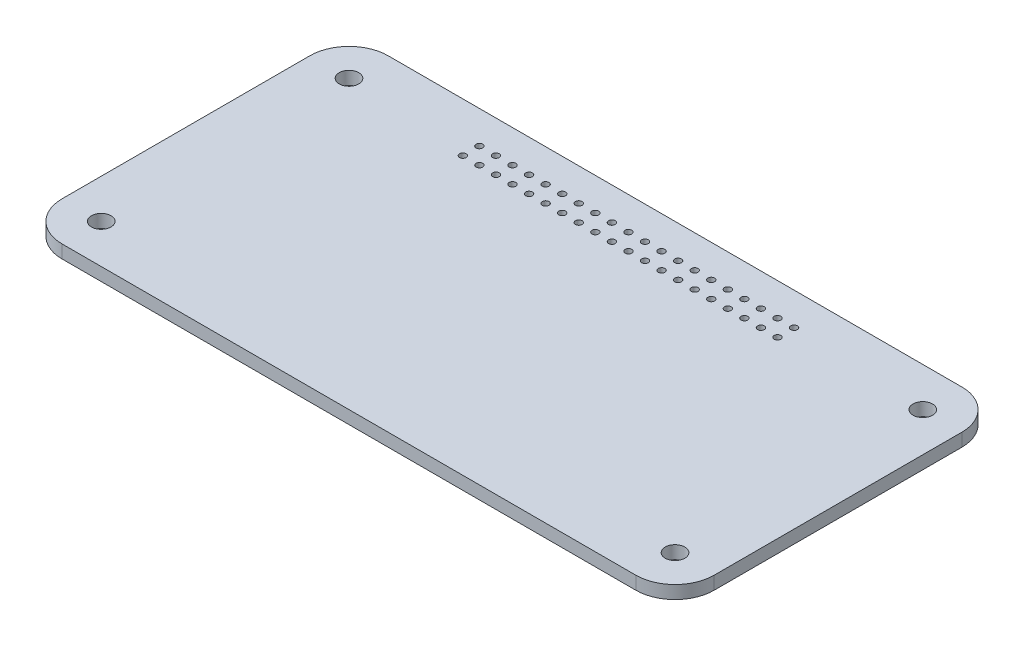
SolidWorks part; units mm, degrees
ref_plane "Front Plane" through (0, 0, 0) normal (0, 0, 1) x (1, 0, 0)
ref_plane "Top Plane" through (0, 0, 0) normal (0, 1, 0) x (1, 0, 0)
ref_plane "Right Plane" through (0, 0, 0) normal (1, 0, 0) x (0, 0, -1)
sketch "Sketch1" plane through (0, 0, 0) normal (0, 1, 0) x (1, 0, 0)
  line L1 (-50, -25) -> (50, -25)
  line L2 (-50, -25) -> (-50, 25)
  line L3 (-50, 25) -> (50, 25)
  line L4 (50, -25) -> (50, 25)
  line L5 (-50, -25) -> (50, 25) construction
  line L6 (-50, 25) -> (50, -25) construction
  point P0 (0, 0)
  dimension "D1" = 100
  dimension "D2" = 50
extrude "Boss-Extrude1" add sketch "Sketch1" along normal blind 2
fillet "Fillet1" radius 6 4 edges at (-50, 1, -25) (-50, 1, 25) (50, 1, -25) (50, 1, 25)
sketch "Sketch2" plane through (0, 2, 0) normal (0, 1, 0) x (1, 0, 0)
  line L0 (44, 25) -> (-44, 25) construction
  line L1 (-44, -19) -> (44, -19)
  line L2 (-44, -19) -> (-44, 19)
  line L3 (-44, 19) -> (44, 19)
  line L4 (44, -19) -> (44, 19)
  line L5 (-44, -19) -> (44, 19) construction
  line L6 (-44, 19) -> (44, -19) construction
  line L7 (50, -19) -> (50, 19) construction
  point P0 (0, 0)
  dimension "D1" = 6
  dimension "D2" = 6
hole_wizard "Ø3.0mm Dowel Hole1" positions "3DSketch1" profile "Sketch3" hole size "Ø3.0" standard "ISO" end condition up to next
sketch3d "3DSketch1"
  point P0 (-44, 2, -19)
  point P3 (44, 2, -19)
  point P6 (44, 2, 19)
  point P9 (-44, 2, 19)
sketch "Sketch3" plane through (-44, 2, -19) normal (1, 0, 0) x (0, 0, 1)
  line L0 (0, 0) -> (0, 2)
  line L1 (0, 2) -> (1.5, 2)
  line L2 (1.5, 2) -> (1.5, 0)
  line L5 (1.5, 0) -> (0, 0)
  line L11 (0, -6.35) -> (0, 107.95) construction
  dimension "Thru Hole Dia." = 3
  dimension "Thru Hole Depth" = 2
sketch "Sketch4" plane through (0, 2, 0) normal (0, 1, 0) x (1, 0, 0)
  line L0 (0, 0) -> (-25, 0)
  line L1 (-25, 0) -> (-25, 20)
  dimension "D1" = 20
  dimension "D2" = 25
hole_wizard "Ø1.0mm Dowel Hole1" positions "3DSketch2" profile "Sketch5" hole size "Ø1.0" standard "ISO" end condition up to next
sketch3d "3DSketch2"
  point P0 (-25, 2, -20)
sketch "Sketch5" plane through (-25, 2, -20) normal (1, 0, 0) x (0, 0, 1)
  line L0 (0, 0) -> (0, 2.001)
  line L1 (0, 2.001) -> (0.51, 2.001)
  line L2 (0.51, 2.001) -> (0.51, 0)
  line L5 (0.51, 0) -> (0, 0)
  line L11 (0, -6.35) -> (0, 107.95) construction
  dimension "Thru Hole Dia." = 1.02
  dimension "Thru Hole Depth" = 2.001
pattern_linear "LPattern1" count 2 spacing 2.54 along (0, 0, 1) count 20 spacing 2.54 along (1, 0, 0) of "Ø1.0mm Dowel Hole1"
